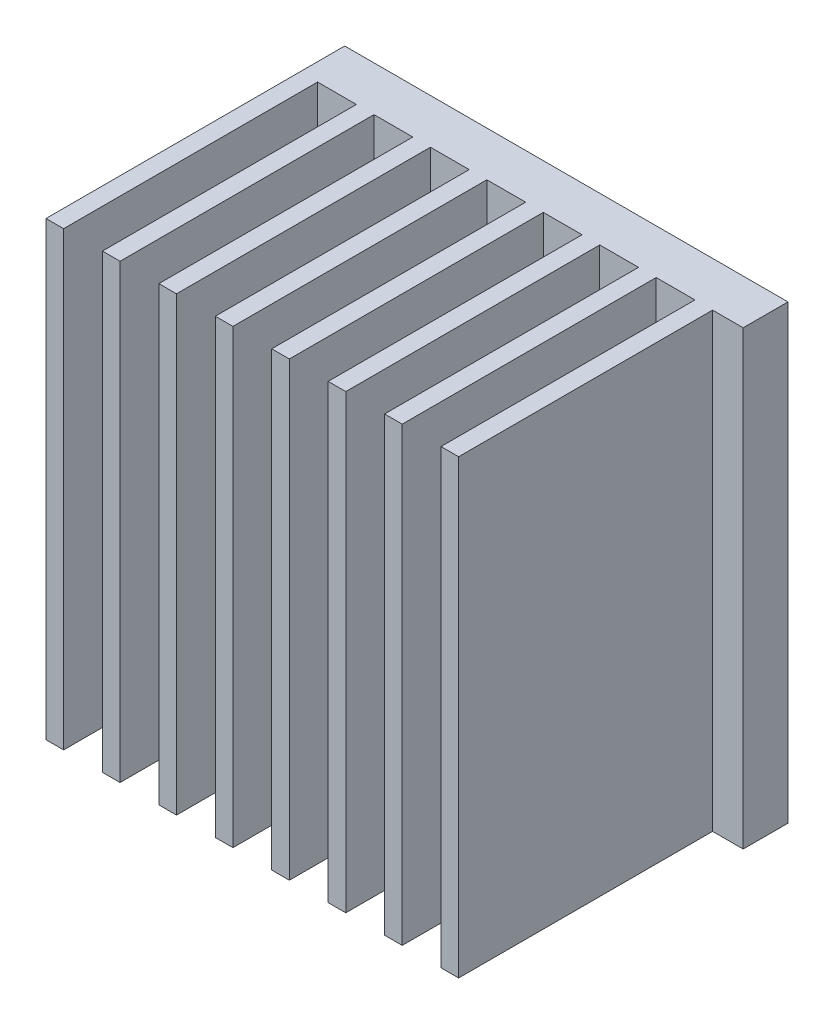
SolidWorks part; units mm, degrees
material "6063-T6"
ref_plane "X-Y Datum" through (0, 0, 0) normal (0, 0, 1) x (1, 0, 0)
ref_plane "X-Z Datum" through (0, 0, 0) normal (0, 1, 0) x (1, 0, 0)
ref_plane "Y-Z Datum" through (0, 0, 0) normal (1, 0, 0) x (0, 0, -1)
sketch "Sketch1" plane through (0, 0, 0) normal (0, 0, 1) x (1, 0, 0)
  line L1 (-15.71, -16) -> (15.71, -16)
  line L2 (-15.71, -16) -> (-15.71, 16)
  line L3 (-15.71, 16) -> (15.71, 16)
  line L4 (15.71, -16) -> (15.71, 16)
  line L5 (-15.71, -16) -> (15.71, 16) construction
  line L6 (-15.71, 16) -> (15.71, -16) construction
  point P0 (0, 0)
  dimension "D1" = 31.42
  dimension "D2" = 32
extrude "Boss-Extrude1" add sketch "Sketch1" along normal blind 3.175
sketch "Sketch2" plane through (0, 0, 3.175) normal (0, 0, 1) x (1, 0, 0)
  line L0 (-15.71, -16) -> (15.71, -16) construction
  line L1 (-15.71, 16) -> (-14.46, 16)
  line L2 (-15.71, 16) -> (-15.71, -16)
  line L3 (-15.71, -16) -> (-14.46, -16)
  line L4 (-14.46, 16) -> (-14.46, -16)
  dimension "D1" = 1.25
extrude "Boss-Extrude2" add sketch "Sketch2" along normal blind 18
pattern_linear "LPattern1" count 8 spacing 4 along (1, 0, 0) of "Boss-Extrude2"
